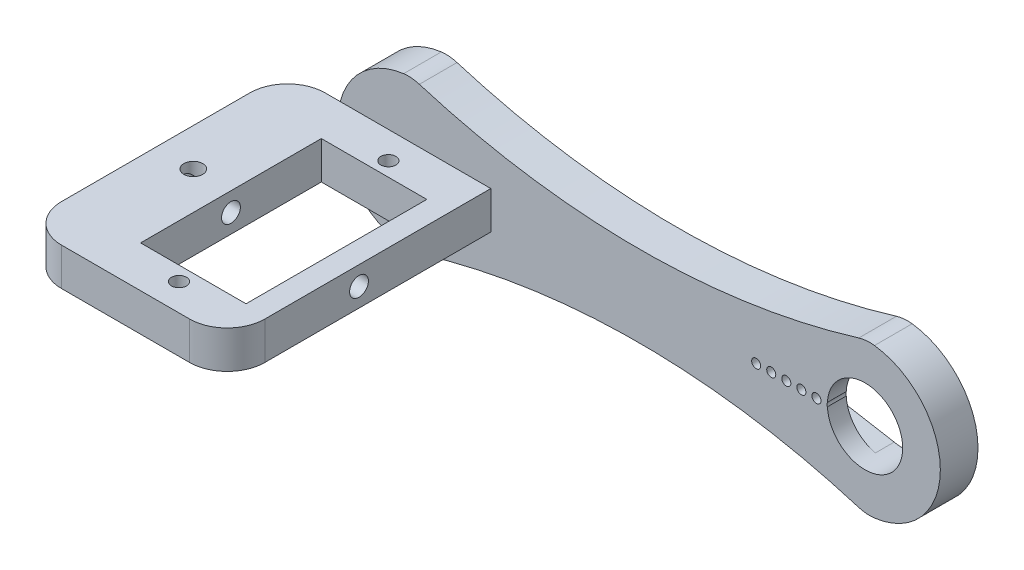
SolidWorks part; units mm, degrees
ref_plane "前视基准面" through (0, 0, 0) normal (0, 0, 1) x (1, 0, 0)
ref_plane "上视基准面" through (0, 0, 0) normal (0, 1, 0) x (1, 0, 0)
ref_plane "右视基准面" through (0, 0, 0) normal (1, 0, 0) x (0, 0, -1)
other "Configuration Table"
sketch "Sketch1" plane through (0, 0, 0) normal (0, 0, 1) x (1, 0, 0)
  line L0 (0, 0) -> (60, 0) construction
  arc A0 (0, 10) -> (0, -10) centre (0, 0) ccw
  circle A1 centre (0, 0) radius 5
  arc A3 (60, -10) -> (60, 10) centre (60, 0) ccw
  circle A4 centre (60, 0) radius 5
  arc A5 (0, 10) -> (60, 10) centre (30, 105.3939) ccw
  arc A6 (0, -10) -> (60, -10) centre (30, -105.3939) cw
  dimension "D1" = 20
  dimension "D2" = 10
  dimension "D3" = 20
  dimension "D4" = 10
  dimension "D6" = 100
  dimension "D5" = 60
extrude "Boss-Extrude1" add sketch "Sketch1" along normal blind 5
fillet "Fillet1" radius 5 4 edges at (60, 10, 2.5) (60, -10, 2.5) (0, -10, 2.5) (0, 10, 2.5)
sketch "Sketch2" plane through (0, 0, 0) normal (0, 0, -1) x (-1, 0, 0)
  line L0 (0, 0) -> (-4.45, 0) construction
  circle A0 centre (-4.45, 0) radius 0.6
  circle A1 centre (-6.45, 0) radius 0.6
  circle A2 centre (-8.45, 0) radius 0.6
  circle A3 centre (-10.45, 0) radius 0.6
  circle A4 centre (-12.45, 0) radius 0.6
  circle A5 centre (-14.45, 0) radius 0.6
  dimension "D1" = 1.2
  dimension "D2" = 4.45
  dimension "D3" = 6
extrude "Cut-Extrude1" cut sketch "Sketch2" against normal blind 5
sketch "Sketch3" plane through (0, 0, 0) normal (0, 0, -1) x (-1, 0, 0)
  line L0 (-14.8825, 2.4623) -> (-0.8651, 4.9246)
  line L1 (-14.45, 0) -> (0, 0) construction
  line L2 (-15.0123, -2.4359) -> (-1.1246, -4.8719)
  circle A0 centre (-14.45, 0) radius 2.5
  circle A1 centre (0, 0) radius 5
  arc A2 (-4.9935, -0.2541) -> (-4.9935, 0.2541) centre (0, 0) ccw construction
  dimension "D1" = 5
extrude "Cut-Extrude2" cut sketch "Sketch3" against normal blind 2.5
sketch "Sketch4" plane through (0, 0, 0) normal (0, 0, -1) x (-1, 0, 0)
  line L0 (0, 0) -> (-60, 0) construction
ref_plane "Plane1" through (30, 0, 0) normal (1, 0, 0) x (0, 0, -1)
mirror "Mirror2" about plane through (30, 0, 0) normal (1, 0, 0) of "Cut-Extrude2", "Cut-Extrude1"
sketch "Sketch11" plane through (0, 0, 0) normal (0, 0, -1) x (-1, 0, 0)
  line L0 (-14.8825, 2.4623) -> (-0.8651, 4.9246)
  line L1 (-15.0123, -2.4359) -> (0, -5)
  circle A0 centre (0, 0) radius 10
  circle A1 centre (0, 0) radius 5
  circle A2 centre (-14.45, 0) radius 2.5
  arc A3 (-1.1246, -4.8719) -> (-0.8651, 4.9246) centre (0, 0) ccw construction
  arc A4 (-14.8825, 2.4623) -> (-15.0123, -2.4359) centre (-14.45, 0) ccw construction
  line M14 (-14.8825, 2.4623) -> (-0.8651, 4.9246)
  arc M15 (-0.8651, 4.9246) -> (-1.1246, -4.8719) centre (0, 0) cw
  arc M17 (-15.0123, -2.4359) -> (-14.8825, 2.4623) centre (-14.45, 0) cw
extrude "Boss-Extrude7" add sketch "Sketch11" against normal up to surface (5 mm away) contours L1 A2 M14 M17 | A1 L0 A0 L1 | A2 L1 A0 L0 | A1 L1 M15
sketch "Sketch12" plane through (0, 0, 5) normal (0, 0, 1) x (1, 0, 0)
  line L1 (-9.6825, -2.5) -> (10.3175, -2.5)
  line L3 (-9.6825, 2.5) -> (10.3175, 2.5)
  line L4 (10.3175, -2.5) -> (10.3175, 2.5)
  line L5 (-9.7188, -2.3549) -> (10.3175, 2.5) construction
  line L6 (-9.7188, 2.3549) -> (10.3175, -2.5) construction
  arc A16 (61.2568, -9.9207) -> (61.2568, 9.9207) centre (60, 0) ccw
  arc A17 (61.2568, 9.9207) -> (59.1699, 9.7429) centre (60.6284, 4.9604) ccw
  arc A18 (0.8301, 9.7429) -> (59.1699, 9.7429) centre (30, 105.3939) ccw
  arc A19 (0.8301, 9.7429) -> (-1.2568, 9.9207) centre (-0.6284, 4.9604) ccw
  arc A20 (-1.2568, 9.9207) -> (-1.2568, -9.9207) centre (0, 0) ccw
  arc A21 (-1.2568, -9.9207) -> (0.8301, -9.7429) centre (-0.6284, -4.9604) ccw
  arc A22 (59.1699, -9.7429) -> (0.8301, -9.7429) centre (30, -105.3939) ccw
  arc A23 (59.1699, -9.7429) -> (61.2568, -9.9207) centre (60.6284, -4.9604) ccw
  arc A24 (61.2568, -9.9207) -> (61.2568, 9.9207) centre (60, 0) ccw
  arc A25 (61.2568, 9.9207) -> (59.1699, 9.7429) centre (60.6284, 4.9604) ccw
  arc A26 (0.8301, 9.7429) -> (59.1699, 9.7429) centre (30, 105.3939) ccw
  arc A27 (0.8301, 9.7429) -> (-1.2568, 9.9207) centre (-0.6284, 4.9604) ccw
  arc A28 (-1.2568, 9.9207) -> (-1.2568, -9.9207) centre (0, 0) ccw
  arc A29 (-1.2568, -9.9207) -> (0.8301, -9.7429) centre (-0.6284, -4.9604) ccw
  arc A30 (59.1699, -9.7429) -> (0.8301, -9.7429) centre (30, -105.3939) ccw
  arc A31 (59.1699, -9.7429) -> (61.2568, -9.9207) centre (60.6284, -4.9604) ccw
  point P0 (0, 0)
  arc M23 (-1.2568, 9.9207) -> (-1.2568, -9.9207) centre (0, 0) ccw
  dimension "D1" = 5
  dimension "D3" = 20
  dimension "D4" = 9.7188
  dimension "D2" = 0
extrude "Boss-Extrude8" add sketch "Sketch12" along normal blind 35 contours L1 L4 L3 M23
sketch "Sketch13" plane through (0, 2.5, 0) normal (0, 1, 0) x (1, 0, 0)
  line L0 (-9.6825, -22.5) -> (10.3175, -22.5) construction
  line L1 (-9.6825, -40) -> (-9.6825, -5) construction
  line L2 (10.3175, -40) -> (10.3175, -5) construction
  line L3 (10.3175, -22.5) -> (0.3175, -22.5) construction
  line L4 (0.3175, -22.5) -> (0.3175, -8.6) construction
  line L5 (-6.6825, -34.5) -> (7.3175, -34.5)
  line L6 (-6.6825, -34.5) -> (-6.6825, -10.5)
  line L7 (-6.6825, -10.5) -> (7.3175, -10.5)
  line L8 (7.3175, -34.5) -> (7.3175, -10.5)
  line L9 (-6.6825, -34.5) -> (7.3175, -10.5) construction
  line L10 (-6.6825, -10.5) -> (7.3175, -34.5) construction
  circle A0 centre (0.3175, -8.6) radius 1
  circle A1 centre (0.3175, -36.4) radius 1
  dimension "D3" = 2
  dimension "D1" = 14
  dimension "D2" = 24
  dimension "D4" = 13.9
extrude "Cut-Extrude3" cut sketch "Sketch13" against normal through all
sketch "Sketch14" plane through (0, 2.5, 0) normal (0, 1, 0) x (1, 0, 0)
  line L0 (-6.6825, -5) -> (-6.6825, -40)
  line L1 (-9.6825, -5) -> (-1.2568, -5) construction
  line L2 (-9.6825, -40) -> (10.3175, -40) construction
  line L3 (-6.6825, -40) -> (-16.6825, -40)
  line L4 (-16.6825, -40) -> (-16.6825, -5)
  line L5 (-16.6825, -5) -> (-6.6825, -5)
  dimension "D1" = 10
extrude "Boss-Extrude9" add sketch "Sketch14" against normal blind 5
sketch "Sketch15" plane through (0, 2.5, 0) normal (0, 1, 0) x (1, 0, 0)
  line L0 (-16.6825, -22.5) -> (-6.6825, -22.5) construction
  line L1 (-16.6825, -5) -> (-16.6825, -40) construction
  line L2 (-6.6825, -10.5) -> (-6.6825, -34.5) construction
  line L3 (-6.6825, -22.5) -> (-11.6825, -22.5) construction
  line L4 (-11.6825, -22.5) -> (-6.6825, -22.5) construction
  line L5 (-6.6825, -22.5) -> (-9.1825, -22.5) construction
  circle A0 centre (-11.6825, -22.5) radius 1.25
  dimension "D1" = 2.5
extrude "Cut-Extrude4" cut sketch "Sketch15" against normal blind 5
sketch "Sketch16" plane through (-16.6825, 0, 0) normal (-1, 0, 0) x (0, 0, 1)
  line L0 (22.5, 2.5) -> (22.5, -2.5) construction
  line L1 (5, 2.5) -> (40, 2.5) construction
  line L2 (5, -2.5) -> (40, -2.5) construction
  line L3 (22.5, -2.5) -> (22.5, 0) construction
  circle A0 centre (22.5, 0) radius 1.25
  dimension "D1" = 2.5
extrude "Cut-Extrude5" cut sketch "Sketch16" against normal through all
fillet "Fillet2" radius 5 3 edges at (10.3175, 0, 40) (-16.6825, 0, 5) (-16.6825, 0, 40)
